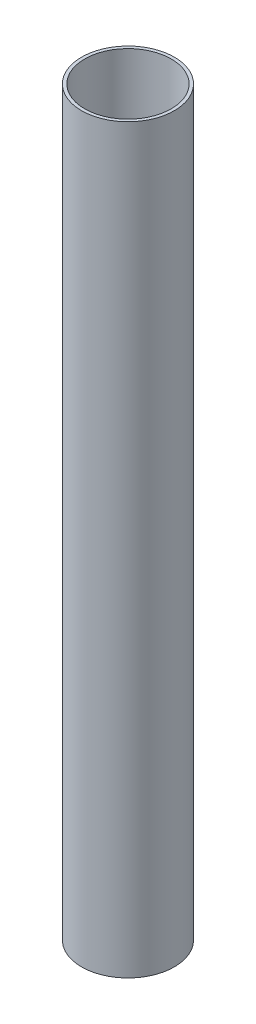
SolidWorks part; units mm, degrees
ref_plane "Front Plane" through (0, 0, 0) normal (0, 0, 1) x (1, 0, 0)
ref_plane "Top Plane" through (0, 0, 0) normal (0, 1, 0) x (1, 0, 0)
ref_plane "Right Plane" through (0, 0, 0) normal (1, 0, 0) x (0, 0, -1)
sketch "Sketch1" plane through (0, 0, 0) normal (0, 1, 0) x (1, 0, 0)
  circle A0 centre (0, 0) radius 37.7
  circle A1 centre (0, 0) radius 35.15
  dimension "D1" = 75.4
  dimension "D2" = 70.3
extrude "Boss-Extrude1" add sketch "Sketch1" along normal blind 602.488
